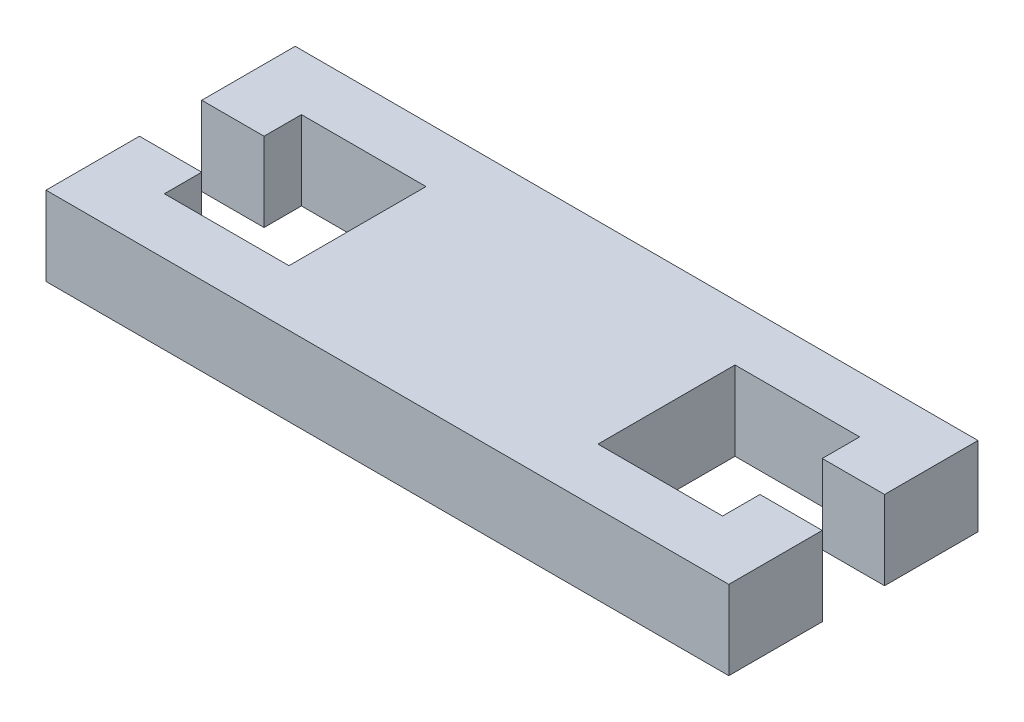
SolidWorks part; units mm, degrees
ref_plane "Front Plane" through (0, 0, 0) normal (0, 0, 1) x (1, 0, 0)
ref_plane "Top Plane" through (0, 0, 0) normal (0, 1, 0) x (1, 0, 0)
ref_plane "Right Plane" through (0, 0, 0) normal (1, 0, 0) x (0, 0, -1)
sketch "Sketch1" plane through (0, 0, 0) normal (0, 1, 0) x (1, 0, 0)
  line L0 (0, 7.5) -> (5, 7.5)
  line L1 (0, 0) -> (54.8, 0)
  line L2 (0, 0) -> (0, 7.5)
  line L3 (0, 20) -> (54.8, 20)
  line L4 (54.8, 0) -> (54.8, 7.5)
  line L5 (5, 15.5) -> (15, 15.5)
  line L6 (15, 15.5) -> (15, 4.5)
  line L7 (15, 4.5) -> (5, 4.5)
  line L8 (27.4, 20) -> (27.4, 0) construction
  line L9 (49.8, 15.5) -> (49.8, 12.5)
  line L10 (54.8, 7.5) -> (49.8, 7.5)
  line L11 (49.8, 4.5) -> (49.8, 7.5)
  line L12 (5, 15.5) -> (5, 12.5)
  line L13 (5, 12.5) -> (0, 12.5)
  line L14 (5, 4.5) -> (5, 7.5)
  line L15 (54.8, 12.5) -> (54.8, 20)
  line L16 (39.8, 4.5) -> (49.8, 4.5)
  line L17 (39.8, 15.5) -> (39.8, 4.5)
  line L18 (49.8, 15.5) -> (39.8, 15.5)
  line L19 (49.8, 12.5) -> (54.8, 12.5)
  line L20 (0, 12.5) -> (0, 20)
  line L21 (15, 10) -> (27.4, 10) construction
  dimension "D1" = 54.8
  dimension "D2" = 5
  dimension "D3" = 20
  dimension "D4" = 7.5
  dimension "D5" = 11
  dimension "D6" = 5
  dimension "D7" = 10
extrude "Boss-Extrude1" add sketch "Sketch1" along normal blind 6.35
